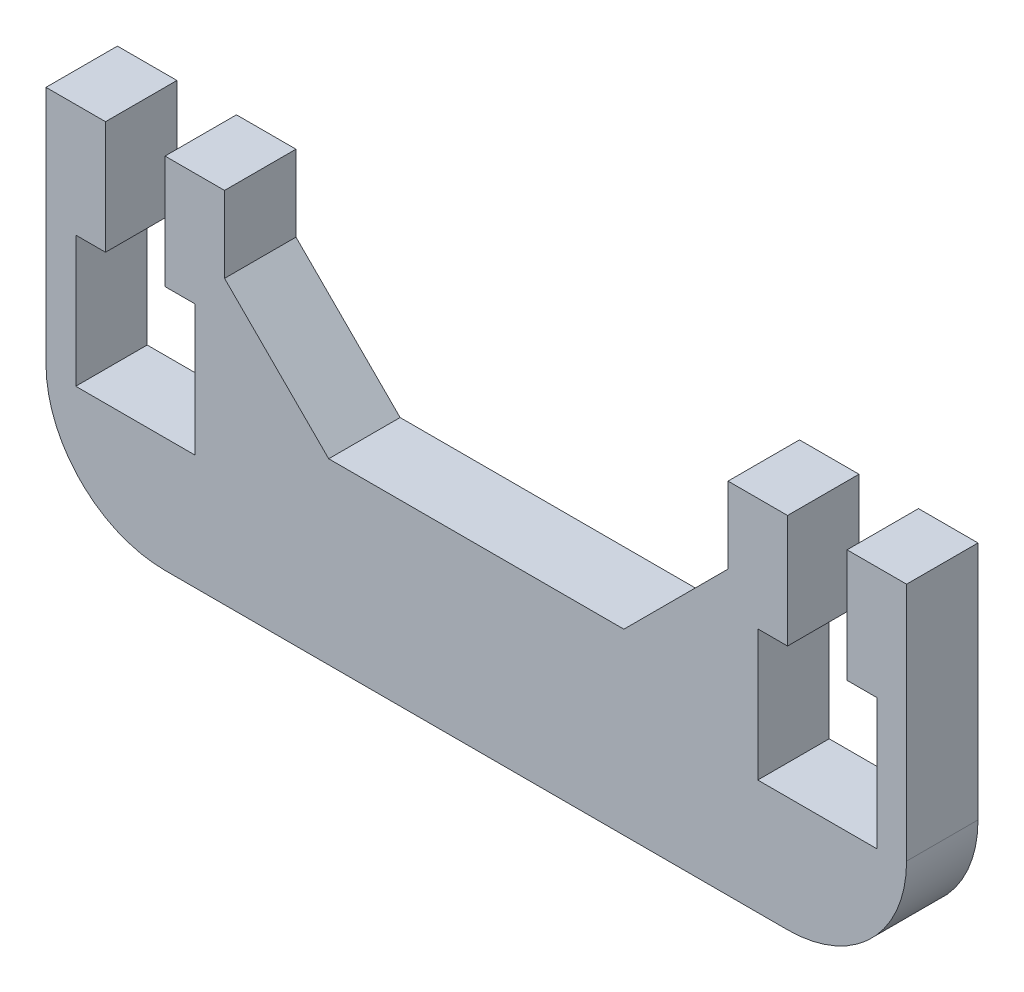
SolidWorks part; units mm, degrees
material "Pine"
ref_plane "Front Plane" through (0, 0, 0) normal (0, 0, 1) x (1, 0, 0)
ref_plane "Top Plane" through (0, 0, 0) normal (0, 1, 0) x (1, 0, 0)
ref_plane "Right Plane" through (0, 0, 0) normal (1, 0, 0) x (0, 0, -1)
sketch "Sketch1" plane through (0, 0, 0) normal (0, 0, 1) x (1, 0, 0)
  line L0 (0, 0) -> (42.3, 0)
  line L1 (42.3, 0) -> (42.3, 15.15)
  line L2 (0, 0) -> (0, 15.15)
  line L3 (-15, -15) -> (-15, 15.15)
  line L4 (-15, -15) -> (57.3, -15)
  line L5 (57.3, -15) -> (57.3, 15.15)
  line L6 (-15, 15.15) -> (0, 15.15)
  line L7 (42.3, 15.15) -> (57.3, 15.15)
  dimension "D1" = 15.15
  dimension "D2" = 42.3
  dimension "D3" = 15
extrude "Boss-Extrude1" add sketch "Sketch1" along normal blind 6
fillet "Fillet1" radius 10 2 edges at (57.3, -15, 3) (-15, -15, 3)
ref_plane "Plane1" through (21.15, 0, 0) normal (1, 0, 0) x (0, 0, -1)
sketch "Sketch2" plane through (0, 0, 0) normal (0, 0, -1) x (-1, 0, 0)
  line L0 (-57.3, 15.15) -> (-42.3, 15.15) construction
  line L1 (-52.3, 15.15) -> (-47.3, 15.15)
  line L2 (-52.3, 15.15) -> (-52.3, 5.65)
  line L3 (-52.3, 5.65) -> (-47.3, 5.65)
  line L4 (-47.3, 15.15) -> (-47.3, 5.65)
  line L6 (-54.8, 5.65) -> (-44.8, 5.65)
  line L7 (-54.8, 5.65) -> (-54.8, -5.35)
  line L8 (-54.8, -5.35) -> (-44.8, -5.35)
  line L9 (-44.8, 5.65) -> (-44.8, -5.35)
  point P10 (-49.8, 15.15)
  point P11 (-49.8, 15.15)
  point P12 (-49.8, 5.65)
  point P13 (-49.8, 5.65)
  dimension "D1" = 9.5
  dimension "D2" = 5
  dimension "D3" = 10
  dimension "D4" = 11
extrude "Cut-Extrude1" cut sketch "Sketch2" against normal through all contours L9 L6 L3 L7 L8
mirror "Mirror1" about plane through (21.15, 0, 0) normal (1, 0, 0) of "Cut-Extrude1"
chamfer "Chamfer1" distance 8.75 angle 45 2 edges at (0, 0, 3) (42.3, 0, 3)
